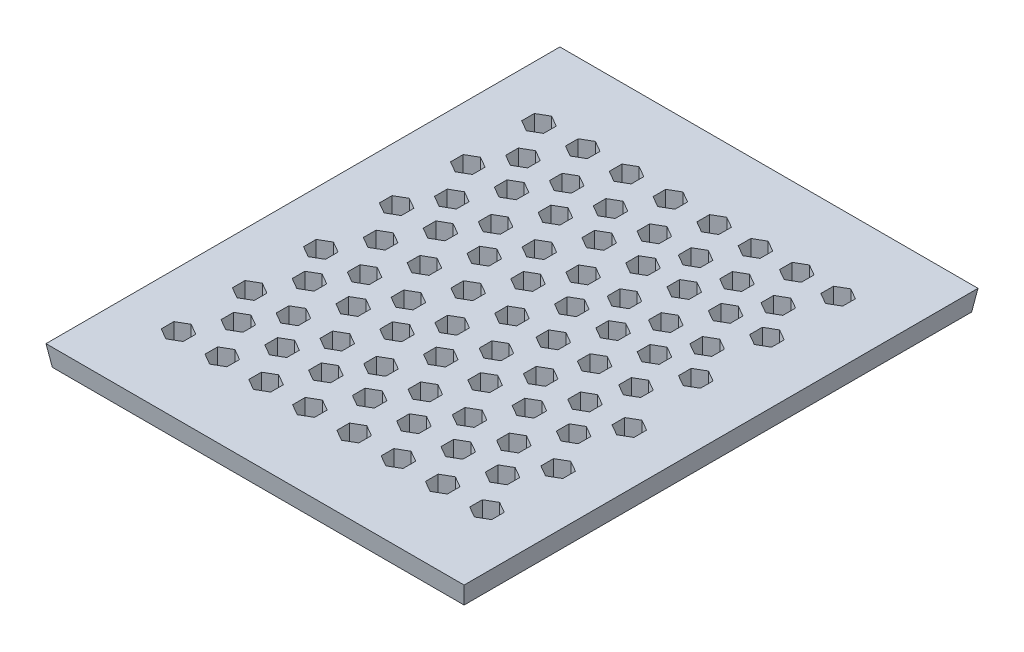
SolidWorks part; units mm, degrees
ref_plane "Front Plane" through (0, 0, 0) normal (0, 0, 1) x (1, 0, 0)
ref_plane "Top Plane" through (0, 0, 0) normal (0, 1, 0) x (1, 0, 0)
ref_plane "Right Plane" through (0, 0, 0) normal (1, 0, 0) x (0, 0, -1)
sketch "Sketch1" plane through (0, 0, 0) normal (0, 1, 0) x (1, 0, 0)
  line L1 (-76.3845, 93.8845) -> (76.3844, 93.8845)
  line L2 (-76.3845, 93.8845) -> (-76.3844, -93.8845)
  line L3 (-76.3844, -93.8845) -> (76.3845, -93.8845)
  line L4 (76.3844, 93.8845) -> (76.3845, -93.8845)
  line L5 (-76.3845, 93.8845) -> (76.3845, -93.8845) construction
  line L6 (-76.3844, -93.8845) -> (76.3844, 93.8845) construction
  point P0 (0, 0)
  dimension "D1" = 187.7689
  dimension "D2" = 152.7689
extrude "Boss-Extrude1" add sketch "Sketch1" against normal blind 7.5 draft 8.77
sketch "Sketch2" plane through (0, 0, 0) normal (0, 1, 0) x (1, 0, 0)
  line L1038 (15.1006, -4.6188) -> (19.1006, -2.3094)
  line L1039 (0, -4.6188) -> (4, -2.3094)
  line L1040 (4, -2.3094) -> (4, 2.3094)
  line L1041 (4, 2.3094) -> (0, 4.6188)
  line L1042 (0, 4.6188) -> (-4, 2.3094)
  line L1043 (-4, 2.3094) -> (-4, -2.3094)
  line L1044 (-4, -2.3094) -> (0, -4.6188)
  line L1045 (11.1006, -2.3094) -> (15.1006, -4.6188)
  line L1046 (8, 18.4752) -> (4, 16.1658)
  line L1047 (4, 16.1658) -> (4, 11.547)
  line L1048 (4, 11.547) -> (8, 9.2376)
  line L1049 (8, 9.2376) -> (12, 11.547)
  line L1050 (12, 11.547) -> (12, 16.1658)
  line L1051 (12, 16.1658) -> (8, 18.4752)
  line L1052 (11.1006, 2.3094) -> (11.1006, -2.3094)
  line L1053 (15.1006, 4.6188) -> (11.1006, 2.3094)
  line L1054 (19.1006, 2.3094) -> (15.1006, 4.6188)
  line L1055 (19.1006, -2.3094) -> (19.1006, 2.3094)
  line L1056 (19.1006, 11.547) -> (23.1006, 9.2376)
  line L1057 (19.1006, 16.1658) -> (19.1006, 11.547)
  line L1058 (23.1006, 18.4752) -> (19.1006, 16.1658)
  line L1059 (27.1006, 16.1658) -> (23.1006, 18.4752)
  line L1060 (27.1006, 11.547) -> (27.1006, 16.1658)
  line L1061 (23.1006, 9.2376) -> (27.1006, 11.547)
  line L1062 (30.2012, -4.6188) -> (34.2012, -2.3094)
  line L1063 (26.2012, -2.3094) -> (30.2012, -4.6188)
  line L1064 (26.2012, 2.3094) -> (26.2012, -2.3094)
  line L1065 (30.2012, 4.6188) -> (26.2012, 2.3094)
  line L1066 (34.2012, 2.3094) -> (30.2012, 4.6188)
  line L1067 (34.2012, -2.3094) -> (34.2012, 2.3094)
  line L1068 (34.2012, 11.547) -> (38.2012, 9.2376)
  line L1069 (34.2012, 16.1658) -> (34.2012, 11.547)
  line L1070 (38.2012, 18.4752) -> (34.2012, 16.1658)
  line L1071 (42.2012, 16.1658) -> (38.2012, 18.4752)
  line L1072 (42.2012, 11.547) -> (42.2012, 16.1658)
  line L1073 (38.2012, 9.2376) -> (42.2012, 11.547)
  line L1074 (45.3017, -4.6188) -> (49.3017, -2.3094)
  line L1075 (41.3017, -2.3094) -> (45.3017, -4.6188)
  line L1076 (41.3017, 2.3094) -> (41.3017, -2.3094)
  line L1077 (45.3017, 4.6188) -> (41.3017, 2.3094)
  line L1078 (49.3017, 2.3094) -> (45.3017, 4.6188)
  line L1079 (49.3017, -2.3094) -> (49.3017, 2.3094)
  line L1080 (49.3017, 11.547) -> (53.3017, 9.2376)
  line L1081 (49.3017, 16.1658) -> (49.3017, 11.547)
  line L1082 (53.3017, 18.4752) -> (49.3017, 16.1658)
  line L1083 (57.3017, 16.1658) -> (53.3017, 18.4752)
  line L1084 (57.3017, 11.547) -> (57.3017, 16.1658)
  line L1085 (53.3017, 9.2376) -> (57.3017, 11.547)
  line L1086 (15.1006, 21.3812) -> (19.1006, 23.6906)
  line L1087 (11.1006, 23.6906) -> (15.1006, 21.3812)
  line L1088 (11.1006, 28.3094) -> (11.1006, 23.6906)
  line L1089 (15.1006, 30.6188) -> (11.1006, 28.3094)
  line L1090 (19.1006, 28.3094) -> (15.1006, 30.6188)
  line L1091 (19.1006, 23.6906) -> (19.1006, 28.3094)
  line L1092 (19.1006, 37.547) -> (23.1006, 35.2376)
  line L1093 (19.1006, 42.1658) -> (19.1006, 37.547)
  line L1094 (23.1006, 44.4752) -> (19.1006, 42.1658)
  line L1095 (27.1006, 42.1658) -> (23.1006, 44.4752)
  line L1096 (27.1006, 37.547) -> (27.1006, 42.1658)
  line L1097 (23.1006, 35.2376) -> (27.1006, 37.547)
  line L1098 (30.2012, 21.3812) -> (34.2012, 23.6906)
  line L1099 (26.2012, 23.6906) -> (30.2012, 21.3812)
  line L1100 (26.2012, 28.3094) -> (26.2012, 23.6906)
  line L1101 (30.2012, 30.6188) -> (26.2012, 28.3094)
  line L1102 (34.2012, 28.3094) -> (30.2012, 30.6188)
  line L1103 (34.2012, 23.6906) -> (34.2012, 28.3094)
  line L1104 (34.2012, 37.547) -> (38.2012, 35.2376)
  line L1105 (34.2012, 42.1658) -> (34.2012, 37.547)
  line L1106 (38.2012, 44.4752) -> (34.2012, 42.1658)
  line L1107 (42.2012, 42.1658) -> (38.2012, 44.4752)
  line L1108 (42.2012, 37.547) -> (42.2012, 42.1658)
  line L1109 (38.2012, 35.2376) -> (42.2012, 37.547)
  line L1110 (45.3017, 21.3812) -> (49.3017, 23.6906)
  line L1111 (41.3017, 23.6906) -> (45.3017, 21.3812)
  line L1112 (41.3017, 28.3094) -> (41.3017, 23.6906)
  line L1113 (45.3017, 30.6188) -> (41.3017, 28.3094)
  line L1114 (49.3017, 28.3094) -> (45.3017, 30.6188)
  line L1115 (49.3017, 23.6906) -> (49.3017, 28.3094)
  line L1116 (49.3017, 37.547) -> (53.3017, 35.2376)
  line L1117 (49.3017, 42.1658) -> (49.3017, 37.547)
  line L1118 (53.3017, 44.4752) -> (49.3017, 42.1658)
  line L1119 (57.3017, 42.1658) -> (53.3017, 44.4752)
  line L1120 (57.3017, 37.547) -> (57.3017, 42.1658)
  line L1121 (53.3017, 35.2376) -> (57.3017, 37.547)
  line L1122 (15.1006, 47.3812) -> (19.1006, 49.6906)
  line L1123 (11.1006, 49.6906) -> (15.1006, 47.3812)
  line L1124 (11.1006, 54.3094) -> (11.1006, 49.6906)
  line L1125 (15.1006, 56.6188) -> (11.1006, 54.3094)
  line L1126 (19.1006, 54.3094) -> (15.1006, 56.6188)
  line L1127 (19.1006, 49.6906) -> (19.1006, 54.3094)
  line L1128 (19.1006, 63.547) -> (23.1006, 61.2376)
  line L1129 (19.1006, 68.1658) -> (19.1006, 63.547)
  line L1130 (23.1006, 70.4752) -> (19.1006, 68.1658)
  line L1131 (27.1006, 68.1658) -> (23.1006, 70.4752)
  line L1132 (27.1006, 63.547) -> (27.1006, 68.1658)
  line L1133 (23.1006, 61.2376) -> (27.1006, 63.547)
  line L1134 (30.2012, 47.3812) -> (34.2012, 49.6906)
  line L1135 (26.2012, 49.6906) -> (30.2012, 47.3812)
  line L1136 (26.2012, 54.3094) -> (26.2012, 49.6906)
  line L1137 (30.2012, 56.6188) -> (26.2012, 54.3094)
  line L1138 (34.2012, 54.3094) -> (30.2012, 56.6188)
  line L1139 (34.2012, 49.6906) -> (34.2012, 54.3094)
  line L1140 (34.2012, 63.547) -> (38.2012, 61.2376)
  line L1141 (34.2012, 68.1658) -> (34.2012, 63.547)
  line L1142 (38.2012, 70.4752) -> (34.2012, 68.1658)
  line L1143 (42.2012, 68.1658) -> (38.2012, 70.4752)
  line L1144 (42.2012, 63.547) -> (42.2012, 68.1658)
  line L1145 (38.2012, 61.2376) -> (42.2012, 63.547)
  line L1146 (45.3017, 47.3812) -> (49.3017, 49.6906)
  line L1147 (41.3017, 49.6906) -> (45.3017, 47.3812)
  line L1148 (41.3017, 54.3094) -> (41.3017, 49.6906)
  line L1149 (45.3017, 56.6188) -> (41.3017, 54.3094)
  line L1150 (49.3017, 54.3094) -> (45.3017, 56.6188)
  line L1151 (49.3017, 49.6906) -> (49.3017, 54.3094)
  line L1152 (49.3017, 63.547) -> (53.3017, 61.2376)
  line L1153 (49.3017, 68.1658) -> (49.3017, 63.547)
  line L1154 (53.3017, 70.4752) -> (49.3017, 68.1658)
  line L1155 (57.3017, 68.1658) -> (53.3017, 70.4752)
  line L1156 (57.3017, 63.547) -> (57.3017, 68.1658)
  line L1157 (53.3017, 61.2376) -> (57.3017, 63.547)
  line L1159 (-4, 23.6906) -> (0, 21.3812)
  line L1160 (-4, 28.3094) -> (-4, 23.6906)
  line L1161 (0, 30.6188) -> (-4, 28.3094)
  line L1162 (4, 28.3094) -> (0, 30.6188)
  line L1163 (4, 23.6906) -> (4, 28.3094)
  line L1164 (4, 37.547) -> (8, 35.2376)
  line L1165 (4, 42.1658) -> (4, 37.547)
  line L1166 (8, 44.4752) -> (4, 42.1658)
  line L1167 (12, 42.1658) -> (8, 44.4752)
  line L1168 (12, 37.547) -> (12, 42.1658)
  line L1170 (0, 47.3812) -> (4, 49.6906)
  line L1171 (-4, 49.6906) -> (0, 47.3812)
  line L1172 (-4, 54.3094) -> (-4, 49.6906)
  line L1174 (4, 54.3094) -> (0, 56.6188)
  line L1175 (4, 49.6906) -> (4, 54.3094)
  line L1176 (4, 63.547) -> (8, 61.2376)
  line L1178 (8, 70.4752) -> (4, 68.1658)
  line L1179 (12, 68.1658) -> (8, 70.4752)
  line L1180 (12, 63.547) -> (12, 68.1658)
  line L1181 (8, 61.2376) -> (12, 63.547)
  line L1182 (-20, -2.3094) -> (-16, -4.6188)
  line L1183 (-20, 2.3094) -> (-20, -2.3094)
  line L1184 (-16, 4.6188) -> (-20, 2.3094)
  line L1185 (-12, 2.3094) -> (-16, 4.6188)
  line L1186 (-16, -4.6188) -> (-12, -2.3094)
  line L1187 (-12, -2.3094) -> (-12, 2.3094)
  line L1188 (-12, 11.547) -> (-8, 9.2376)
  line L1189 (-12, 16.1658) -> (-12, 11.547)
  line L1190 (-8, 18.4752) -> (-12, 16.1658)
  line L1191 (-4, 16.1658) -> (-8, 18.4752)
  line L1192 (-4, 11.547) -> (-4, 16.1658)
  line L1193 (-8, 9.2376) -> (-4, 11.547)
  line L1194 (-36, -2.3094) -> (-32, -4.6188)
  line L1195 (-36, 2.3094) -> (-36, -2.3094)
  line L1196 (-32, 4.6188) -> (-36, 2.3094)
  line L1197 (-28, 2.3094) -> (-32, 4.6188)
  line L1198 (-32, -4.6188) -> (-28, -2.3094)
  line L1199 (-28, -2.3094) -> (-28, 2.3094)
  line L1200 (-28, 11.547) -> (-24, 9.2376)
  line L1201 (-28, 16.1658) -> (-28, 11.547)
  line L1202 (-24, 18.4752) -> (-28, 16.1658)
  line L1203 (-20, 16.1658) -> (-24, 18.4752)
  line L1204 (-20, 11.547) -> (-20, 16.1658)
  line L1205 (-24, 9.2376) -> (-20, 11.547)
  line L1206 (-52, -2.3094) -> (-48, -4.6188)
  line L1207 (-52, 2.3094) -> (-52, -2.3094)
  line L1208 (-48, 4.6188) -> (-52, 2.3094)
  line L1209 (-44, 2.3094) -> (-48, 4.6188)
  line L1210 (-48, -4.6188) -> (-44, -2.3094)
  line L1211 (-44, -2.3094) -> (-44, 2.3094)
  line L1212 (-44, 11.547) -> (-40, 9.2376)
  line L1213 (-44, 16.1658) -> (-44, 11.547)
  line L1214 (-40, 18.4752) -> (-44, 16.1658)
  line L1215 (-36, 16.1658) -> (-40, 18.4752)
  line L1216 (-36, 11.547) -> (-36, 16.1658)
  line L1217 (-40, 9.2376) -> (-36, 11.547)
  line L1224 (-60, 11.547) -> (-56, 9.2376)
  line L1225 (-60, 16.1658) -> (-60, 11.547)
  line L1226 (-56, 18.4752) -> (-60, 16.1658)
  line L1227 (-52, 16.1658) -> (-56, 18.4752)
  line L1228 (-52, 11.547) -> (-52, 16.1658)
  line L1229 (-56, 9.2376) -> (-52, 11.547)
  line L1230 (-20, 23.6906) -> (-16, 21.3812)
  line L1231 (-20, 28.3094) -> (-20, 23.6906)
  line L1232 (-16, 30.6188) -> (-20, 28.3094)
  line L1233 (-12, 28.3094) -> (-16, 30.6188)
  line L1234 (-16, 21.3812) -> (-12, 23.6906)
  line L1235 (-12, 23.6906) -> (-12, 28.3094)
  line L1236 (-12, 37.547) -> (-8, 35.2376)
  line L1237 (-12, 42.1658) -> (-12, 37.547)
  line L1238 (-8, 44.4752) -> (-12, 42.1658)
  line L1239 (-4, 42.1658) -> (-8, 44.4752)
  line L1240 (-4, 37.547) -> (-4, 42.1658)
  line L1241 (-8, 35.2376) -> (-4, 37.547)
  line L1242 (-36, 23.6906) -> (-32, 21.3812)
  line L1243 (-36, 28.3094) -> (-36, 23.6906)
  line L1244 (-32, 30.6188) -> (-36, 28.3094)
  line L1245 (-28, 28.3094) -> (-32, 30.6188)
  line L1246 (-32, 21.3812) -> (-28, 23.6906)
  line L1247 (-28, 23.6906) -> (-28, 28.3094)
  line L1248 (-28, 37.547) -> (-24, 35.2376)
  line L1249 (-28, 42.1658) -> (-28, 37.547)
  line L1250 (-24, 44.4752) -> (-28, 42.1658)
  line L1251 (-20, 42.1658) -> (-24, 44.4752)
  line L1252 (-20, 37.547) -> (-20, 42.1658)
  line L1253 (-24, 35.2376) -> (-20, 37.547)
  line L1254 (-52, 23.6906) -> (-48, 21.3812)
  line L1255 (-52, 28.3094) -> (-52, 23.6906)
  line L1256 (-48, 30.6188) -> (-52, 28.3094)
  line L1257 (-44, 28.3094) -> (-48, 30.6188)
  line L1258 (-48, 21.3812) -> (-44, 23.6906)
  line L1259 (-44, 23.6906) -> (-44, 28.3094)
  line L1260 (-44, 37.547) -> (-40, 35.2376)
  line L1261 (-44, 42.1658) -> (-44, 37.547)
  line L1262 (-40, 44.4752) -> (-44, 42.1658)
  line L1263 (-36, 42.1658) -> (-40, 44.4752)
  line L1264 (-36, 37.547) -> (-36, 42.1658)
  line L1265 (-40, 35.2376) -> (-36, 37.547)
  line L1272 (-60, 37.547) -> (-56, 35.2376)
  line L1273 (-60, 42.1658) -> (-60, 37.547)
  line L1274 (-56, 44.4752) -> (-60, 42.1658)
  line L1275 (-52, 42.1658) -> (-56, 44.4752)
  line L1276 (-52, 37.547) -> (-52, 42.1658)
  line L1277 (-56, 35.2376) -> (-52, 37.547)
  line L1278 (-20, 49.6906) -> (-16, 47.3812)
  line L1279 (-20, 54.3094) -> (-20, 49.6906)
  line L1280 (-16, 56.6188) -> (-20, 54.3094)
  line L1281 (-12, 54.3094) -> (-16, 56.6188)
  line L1282 (-16, 47.3812) -> (-12, 49.6906)
  line L1283 (-12, 49.6906) -> (-12, 54.3094)
  line L1284 (-12, 63.547) -> (-8, 61.2376)
  line L1285 (-12, 68.1658) -> (-12, 63.547)
  line L1286 (-8, 70.4752) -> (-12, 68.1658)
  line L1287 (-4, 68.1658) -> (-8, 70.4752)
  line L1288 (-4, 63.547) -> (-4, 68.1658)
  line L1289 (-8, 61.2376) -> (-4, 63.547)
  line L1290 (-36, 49.6906) -> (-32, 47.3812)
  line L1291 (-36, 54.3094) -> (-36, 49.6906)
  line L1292 (-32, 56.6188) -> (-36, 54.3094)
  line L1293 (-28, 54.3094) -> (-32, 56.6188)
  line L1294 (-32, 47.3812) -> (-28, 49.6906)
  line L1295 (-28, 49.6906) -> (-28, 54.3094)
  line L1296 (-28, 63.547) -> (-24, 61.2376)
  line L1297 (-28, 68.1658) -> (-28, 63.547)
  line L1298 (-24, 70.4752) -> (-28, 68.1658)
  line L1299 (-20, 68.1658) -> (-24, 70.4752)
  line L1300 (-20, 63.547) -> (-20, 68.1658)
  line L1301 (-24, 61.2376) -> (-20, 63.547)
  line L1302 (-52, 49.6906) -> (-48, 47.3812)
  line L1303 (-52, 54.3094) -> (-52, 49.6906)
  line L1304 (-48, 56.6188) -> (-52, 54.3094)
  line L1305 (-44, 54.3094) -> (-48, 56.6188)
  line L1306 (-48, 47.3812) -> (-44, 49.6906)
  line L1307 (-44, 49.6906) -> (-44, 54.3094)
  line L1308 (-44, 63.547) -> (-40, 61.2376)
  line L1309 (-44, 68.1658) -> (-44, 63.547)
  line L1310 (-40, 70.4752) -> (-44, 68.1658)
  line L1311 (-36, 68.1658) -> (-40, 70.4752)
  line L1312 (-36, 63.547) -> (-36, 68.1658)
  line L1313 (-40, 61.2376) -> (-36, 63.547)
  line L1320 (-60, 63.547) -> (-56, 61.2376)
  line L1321 (-60, 68.1658) -> (-60, 63.547)
  line L1322 (-56, 70.4752) -> (-60, 68.1658)
  line L1323 (-52, 68.1658) -> (-56, 70.4752)
  line L1324 (-52, 63.547) -> (-52, 68.1658)
  line L1325 (-56, 61.2376) -> (-52, 63.547)
  line L1330 (0, 21.3812) -> (4, 23.6906)
  line L1337 (8, 35.2376) -> (12, 37.547)
  line L1340 (0, 56.6188) -> (-4, 54.3094)
  line L1345 (4, 68.1658) -> (4, 63.547)
  line L1352 (-68, 49.6906) -> (-64, 47.3812) [skipped]
  line L1353 (-68, 54.3094) -> (-68, 49.6906) [skipped]
  line L1354 (-64, 56.6188) -> (-68, 54.3094) [skipped]
  line L1355 (-60, 54.3094) -> (-64, 56.6188) [skipped]
  line L1356 (-64, 47.3812) -> (-60, 49.6906) [skipped]
  line L1357 (-60, 49.6906) -> (-60, 54.3094) [skipped]
  line L1358 (-68, 23.6906) -> (-64, 21.3812) [skipped]
  line L1359 (-68, 28.3094) -> (-68, 23.6906) [skipped]
  line L1360 (-64, 30.6188) -> (-68, 28.3094) [skipped]
  line L1361 (-60, 28.3094) -> (-64, 30.6188) [skipped]
  line L1362 (-64, 21.3812) -> (-60, 23.6906) [skipped]
  line L1363 (-60, 23.6906) -> (-60, 28.3094) [skipped]
  line L1364 (-68, -2.3094) -> (-64, -4.6188) [skipped]
  line L1365 (-68, 2.3094) -> (-68, -2.3094) [skipped]
  line L1366 (-64, 4.6188) -> (-68, 2.3094) [skipped]
  line L1367 (-60, 2.3094) -> (-64, 4.6188) [skipped]
  line L1368 (-64, -4.6188) -> (-60, -2.3094) [skipped]
  line L1369 (-60, -2.3094) -> (-60, 2.3094) [skipped]
  line L1370 (-8, -9.2376) -> (-12, -11.547)
  line L1371 (-12, -11.547) -> (-12, -16.1658)
  line L1372 (-12, -16.1658) -> (-8, -18.4752)
  line L1373 (-8, -18.4752) -> (-4, -16.1658)
  line L1374 (-4, -16.1658) -> (-4, -11.547)
  line L1375 (-4, -11.547) -> (-8, -9.2376)
  line L1380 (12.1801, -11.547) -> (8.1801, -9.2376)
  line L1381 (8.1801, -9.2376) -> (4.1801, -11.547)
  line L1382 (4.1801, -11.547) -> (4.1801, -16.1658)
  line L1383 (4.1801, -16.1658) -> (8.1801, -18.4752)
  line L1384 (8.1801, -18.4752) -> (12.1801, -16.1658)
  line L1385 (12.1801, -16.1658) -> (12.1801, -11.547)
  line L1392 (28.3602, -11.547) -> (24.3602, -9.2376)
  line L1393 (24.3602, -9.2376) -> (20.3602, -11.547)
  line L1394 (20.3602, -11.547) -> (20.3602, -16.1658)
  line L1395 (20.3602, -16.1658) -> (24.3602, -18.4752)
  line L1396 (24.3602, -18.4752) -> (28.3602, -16.1658)
  line L1397 (28.3602, -16.1658) -> (28.3602, -11.547)
  line L1404 (44.5404, -11.547) -> (40.5404, -9.2376)
  line L1405 (40.5404, -9.2376) -> (36.5404, -11.547)
  line L1406 (36.5404, -11.547) -> (36.5404, -16.1658)
  line L1407 (36.5404, -16.1658) -> (40.5404, -18.4752)
  line L1408 (40.5404, -18.4752) -> (44.5404, -16.1658)
  line L1409 (44.5404, -16.1658) -> (44.5404, -11.547)
  line L1416 (60.7205, -11.547) -> (56.7205, -9.2376)
  line L1417 (56.7205, -9.2376) -> (52.7205, -11.547)
  line L1418 (52.7205, -11.547) -> (52.7205, -16.1658)
  line L1419 (52.7205, -16.1658) -> (56.7205, -18.4752)
  line L1420 (56.7205, -18.4752) -> (60.7205, -16.1658)
  line L1421 (60.7205, -16.1658) -> (60.7205, -11.547)
  line L1422 (12.1801, -28.3094) -> (16.1801, -30.6188)
  line L1423 (12.1801, -23.6906) -> (12.1801, -28.3094)
  line L1424 (16.1801, -21.3812) -> (12.1801, -23.6906)
  line L1425 (20.1801, -23.6906) -> (16.1801, -21.3812)
  line L1426 (20.1801, -28.3094) -> (20.1801, -23.6906)
  line L1427 (16.1801, -30.6188) -> (20.1801, -28.3094)
  line L1428 (12.1801, -37.547) -> (8.1801, -35.2376)
  line L1429 (8.1801, -35.2376) -> (4.1801, -37.547)
  line L1430 (4.1801, -37.547) -> (4.1801, -42.1658)
  line L1431 (4.1801, -42.1658) -> (8.1801, -44.4752)
  line L1432 (8.1801, -44.4752) -> (12.1801, -42.1658)
  line L1433 (12.1801, -42.1658) -> (12.1801, -37.547)
  line L1434 (28.3602, -28.3094) -> (32.3602, -30.6188)
  line L1435 (28.3602, -23.6906) -> (28.3602, -28.3094)
  line L1436 (32.3602, -21.3812) -> (28.3602, -23.6906)
  line L1437 (36.3602, -23.6906) -> (32.3602, -21.3812)
  line L1438 (36.3602, -28.3094) -> (36.3602, -23.6906)
  line L1439 (32.3602, -30.6188) -> (36.3602, -28.3094)
  line L1440 (28.3602, -37.547) -> (24.3602, -35.2376)
  line L1441 (24.3602, -35.2376) -> (20.3602, -37.547)
  line L1442 (20.3602, -37.547) -> (20.3602, -42.1658)
  line L1443 (20.3602, -42.1658) -> (24.3602, -44.4752)
  line L1444 (24.3602, -44.4752) -> (28.3602, -42.1658)
  line L1445 (28.3602, -42.1658) -> (28.3602, -37.547)
  line L1446 (44.5404, -28.3094) -> (48.5404, -30.6188)
  line L1447 (44.5404, -23.6906) -> (44.5404, -28.3094)
  line L1448 (48.5404, -21.3812) -> (44.5404, -23.6906)
  line L1449 (52.5404, -23.6906) -> (48.5404, -21.3812)
  line L1450 (52.5404, -28.3094) -> (52.5404, -23.6906)
  line L1451 (48.5404, -30.6188) -> (52.5404, -28.3094)
  line L1452 (44.5404, -37.547) -> (40.5404, -35.2376)
  line L1453 (40.5404, -35.2376) -> (36.5404, -37.547)
  line L1454 (36.5404, -37.547) -> (36.5404, -42.1658)
  line L1455 (36.5404, -42.1658) -> (40.5404, -44.4752)
  line L1456 (40.5404, -44.4752) -> (44.5404, -42.1658)
  line L1457 (44.5404, -42.1658) -> (44.5404, -37.547)
  line L1464 (60.7205, -37.547) -> (56.7205, -35.2376)
  line L1465 (56.7205, -35.2376) -> (52.7205, -37.547)
  line L1466 (52.7205, -37.547) -> (52.7205, -42.1658)
  line L1467 (52.7205, -42.1658) -> (56.7205, -44.4752)
  line L1468 (56.7205, -44.4752) -> (60.7205, -42.1658)
  line L1469 (60.7205, -42.1658) -> (60.7205, -37.547)
  line L1470 (12.1801, -54.3094) -> (16.1801, -56.6188)
  line L1471 (12.1801, -49.6906) -> (12.1801, -54.3094)
  line L1472 (16.1801, -47.3812) -> (12.1801, -49.6906)
  line L1473 (20.1801, -49.6906) -> (16.1801, -47.3812)
  line L1474 (20.1801, -54.3094) -> (20.1801, -49.6906)
  line L1475 (16.1801, -56.6188) -> (20.1801, -54.3094)
  line L1476 (12.1801, -63.547) -> (8.1801, -61.2376)
  line L1477 (8.1801, -61.2376) -> (4.1801, -63.547)
  line L1478 (4.1801, -63.547) -> (4.1801, -68.1658)
  line L1479 (4.1801, -68.1658) -> (8.1801, -70.4752)
  line L1480 (8.1801, -70.4752) -> (12.1801, -68.1658)
  line L1481 (12.1801, -68.1658) -> (12.1801, -63.547)
  line L1482 (28.3602, -54.3094) -> (32.3602, -56.6188)
  line L1483 (28.3602, -49.6906) -> (28.3602, -54.3094)
  line L1484 (32.3602, -47.3812) -> (28.3602, -49.6906)
  line L1485 (36.3602, -49.6906) -> (32.3602, -47.3812)
  line L1486 (36.3602, -54.3094) -> (36.3602, -49.6906)
  line L1487 (32.3602, -56.6188) -> (36.3602, -54.3094)
  line L1488 (28.3602, -63.547) -> (24.3602, -61.2376)
  line L1489 (24.3602, -61.2376) -> (20.3602, -63.547)
  line L1490 (20.3602, -63.547) -> (20.3602, -68.1658)
  line L1491 (20.3602, -68.1658) -> (24.3602, -70.4752)
  line L1492 (24.3602, -70.4752) -> (28.3602, -68.1658)
  line L1493 (28.3602, -68.1658) -> (28.3602, -63.547)
  line L1494 (44.5404, -54.3094) -> (48.5404, -56.6188)
  line L1495 (44.5404, -49.6906) -> (44.5404, -54.3094)
  line L1496 (48.5404, -47.3812) -> (44.5404, -49.6906)
  line L1497 (52.5404, -49.6906) -> (48.5404, -47.3812)
  line L1498 (52.5404, -54.3094) -> (52.5404, -49.6906)
  line L1499 (48.5404, -56.6188) -> (52.5404, -54.3094)
  line L1500 (44.5404, -63.547) -> (40.5404, -61.2376)
  line L1501 (40.5404, -61.2376) -> (36.5404, -63.547)
  line L1502 (36.5404, -63.547) -> (36.5404, -68.1658)
  line L1503 (36.5404, -68.1658) -> (40.5404, -70.4752)
  line L1504 (40.5404, -70.4752) -> (44.5404, -68.1658)
  line L1505 (44.5404, -68.1658) -> (44.5404, -63.547)
  line L1512 (60.7205, -63.547) -> (56.7205, -61.2376)
  line L1513 (56.7205, -61.2376) -> (52.7205, -63.547)
  line L1514 (52.7205, -63.547) -> (52.7205, -68.1658)
  line L1515 (52.7205, -68.1658) -> (56.7205, -70.4752)
  line L1516 (56.7205, -70.4752) -> (60.7205, -68.1658)
  line L1517 (60.7205, -68.1658) -> (60.7205, -63.547)
  line L1518 (-4, -28.3094) -> (0, -30.6188)
  line L1519 (-4, -23.6906) -> (-4, -28.3094)
  line L1520 (0, -21.3812) -> (-4, -23.6906)
  line L1521 (4, -23.6906) -> (0, -21.3812)
  line L1522 (4, -28.3094) -> (4, -23.6906)
  line L1523 (0, -30.6188) -> (4, -28.3094)
  line L1524 (-4, -37.547) -> (-8, -35.2376)
  line L1525 (-8, -35.2376) -> (-12, -37.547)
  line L1526 (-12, -37.547) -> (-12, -42.1658)
  line L1527 (-12, -42.1658) -> (-8, -44.4752)
  line L1529 (-4, -42.1658) -> (-4, -37.547)
  line L1530 (-4, -54.3094) -> (0, -56.6188)
  line L1531 (-4, -49.6906) -> (-4, -54.3094)
  line L1532 (0, -47.3812) -> (-4, -49.6906)
  line L1533 (4, -49.6906) -> (0, -47.3812)
  line L1534 (4, -54.3094) -> (4, -49.6906)
  line L1536 (-4, -63.547) -> (-8, -61.2376)
  line L1537 (-8, -61.2376) -> (-12, -63.547)
  line L1538 (-12, -63.547) -> (-12, -68.1658)
  line L1539 (-12, -68.1658) -> (-8, -70.4752)
  line L1541 (-4, -68.1658) -> (-4, -63.547)
  line L1542 (-20, -11.547) -> (-24, -9.2376)
  line L1543 (-24, -9.2376) -> (-28, -11.547)
  line L1544 (-28, -11.547) -> (-28, -16.1658)
  line L1545 (-28, -16.1658) -> (-24, -18.4752)
  line L1546 (-24, -18.4752) -> (-20, -16.1658)
  line L1547 (-20, -16.1658) -> (-20, -11.547)
  line L1548 (-20, -23.6906) -> (-20, -28.3094)
  line L1549 (-16, -21.3812) -> (-20, -23.6906)
  line L1550 (-12, -23.6906) -> (-16, -21.3812)
  line L1551 (-12, -28.3094) -> (-12, -23.6906)
  line L1552 (-16, -30.6188) -> (-12, -28.3094)
  line L1553 (-20, -28.3094) -> (-16, -30.6188)
  line L1554 (-36, -11.547) -> (-40, -9.2376)
  line L1555 (-40, -9.2376) -> (-44, -11.547)
  line L1556 (-44, -11.547) -> (-44, -16.1658)
  line L1557 (-44, -16.1658) -> (-40, -18.4752)
  line L1558 (-40, -18.4752) -> (-36, -16.1658)
  line L1559 (-36, -16.1658) -> (-36, -11.547)
  line L1560 (-36, -23.6906) -> (-36, -28.3094)
  line L1561 (-32, -21.3812) -> (-36, -23.6906)
  line L1562 (-28, -23.6906) -> (-32, -21.3812)
  line L1563 (-28, -28.3094) -> (-28, -23.6906)
  line L1564 (-32, -30.6188) -> (-28, -28.3094)
  line L1565 (-36, -28.3094) -> (-32, -30.6188)
  line L1566 (-52, -11.547) -> (-56, -9.2376)
  line L1567 (-56, -9.2376) -> (-60, -11.547)
  line L1568 (-60, -11.547) -> (-60, -16.1658)
  line L1569 (-60, -16.1658) -> (-56, -18.4752)
  line L1570 (-56, -18.4752) -> (-52, -16.1658)
  line L1571 (-52, -16.1658) -> (-52, -11.547)
  line L1572 (-52, -23.6906) -> (-52, -28.3094)
  line L1573 (-48, -21.3812) -> (-52, -23.6906)
  line L1574 (-44, -23.6906) -> (-48, -21.3812)
  line L1575 (-44, -28.3094) -> (-44, -23.6906)
  line L1576 (-48, -30.6188) -> (-44, -28.3094)
  line L1577 (-52, -28.3094) -> (-48, -30.6188)
  line L1578 (-20, -37.547) -> (-24, -35.2376)
  line L1579 (-24, -35.2376) -> (-28, -37.547)
  line L1580 (-28, -37.547) -> (-28, -42.1658)
  line L1581 (-28, -42.1658) -> (-24, -44.4752)
  line L1582 (-24, -44.4752) -> (-20, -42.1658)
  line L1583 (-20, -42.1658) -> (-20, -37.547)
  line L1584 (-20, -49.6906) -> (-20, -54.3094)
  line L1585 (-16, -47.3812) -> (-20, -49.6906)
  line L1586 (-12, -49.6906) -> (-16, -47.3812)
  line L1587 (-12, -54.3094) -> (-12, -49.6906)
  line L1588 (-16, -56.6188) -> (-12, -54.3094)
  line L1589 (-20, -54.3094) -> (-16, -56.6188)
  line L1590 (-36, -37.547) -> (-40, -35.2376)
  line L1591 (-40, -35.2376) -> (-44, -37.547)
  line L1592 (-44, -37.547) -> (-44, -42.1658)
  line L1593 (-44, -42.1658) -> (-40, -44.4752)
  line L1594 (-40, -44.4752) -> (-36, -42.1658)
  line L1595 (-36, -42.1658) -> (-36, -37.547)
  line L1596 (-36, -49.6906) -> (-36, -54.3094)
  line L1597 (-32, -47.3812) -> (-36, -49.6906)
  line L1598 (-28, -49.6906) -> (-32, -47.3812)
  line L1599 (-28, -54.3094) -> (-28, -49.6906)
  line L1600 (-32, -56.6188) -> (-28, -54.3094)
  line L1601 (-36, -54.3094) -> (-32, -56.6188)
  line L1602 (-52, -37.547) -> (-56, -35.2376)
  line L1603 (-56, -35.2376) -> (-60, -37.547)
  line L1604 (-60, -37.547) -> (-60, -42.1658)
  line L1605 (-60, -42.1658) -> (-56, -44.4752)
  line L1606 (-56, -44.4752) -> (-52, -42.1658)
  line L1607 (-52, -42.1658) -> (-52, -37.547)
  line L1608 (-52, -49.6906) -> (-52, -54.3094)
  line L1609 (-48, -47.3812) -> (-52, -49.6906)
  line L1610 (-44, -49.6906) -> (-48, -47.3812)
  line L1611 (-44, -54.3094) -> (-44, -49.6906)
  line L1612 (-48, -56.6188) -> (-44, -54.3094)
  line L1613 (-52, -54.3094) -> (-48, -56.6188)
  line L1614 (-20, -63.547) -> (-24, -61.2376)
  line L1615 (-24, -61.2376) -> (-28, -63.547)
  line L1616 (-28, -63.547) -> (-28, -68.1658)
  line L1617 (-28, -68.1658) -> (-24, -70.4752)
  line L1618 (-24, -70.4752) -> (-20, -68.1658)
  line L1619 (-20, -68.1658) -> (-20, -63.547)
  line L1626 (-36, -63.547) -> (-40, -61.2376)
  line L1627 (-40, -61.2376) -> (-44, -63.547)
  line L1628 (-44, -63.547) -> (-44, -68.1658)
  line L1629 (-44, -68.1658) -> (-40, -70.4752)
  line L1630 (-40, -70.4752) -> (-36, -68.1658)
  line L1631 (-36, -68.1658) -> (-36, -63.547)
  line L1638 (-52, -63.547) -> (-56, -61.2376)
  line L1639 (-56, -61.2376) -> (-60, -63.547)
  line L1640 (-60, -63.547) -> (-60, -68.1658)
  line L1641 (-60, -68.1658) -> (-56, -70.4752)
  line L1642 (-56, -70.4752) -> (-52, -68.1658)
  line L1643 (-52, -68.1658) -> (-52, -63.547)
  line L1654 (-8, -44.4752) -> (-4, -42.1658)
  line L1660 (0, -56.6188) -> (4, -54.3094)
  line L1666 (-8, -70.4752) -> (-4, -68.1658)
  line L1674 (-20, -75.6906) -> (-20, -80.3094) [skipped]
  line L1675 (-16, -73.3812) -> (-20, -75.6906) [skipped]
  line L1676 (-12, -75.6906) -> (-16, -73.3812) [skipped]
  line L1677 (-12, -80.3094) -> (-12, -75.6906) [skipped]
  line L1678 (-16, -82.6188) -> (-12, -80.3094) [skipped]
  line L1679 (-20, -80.3094) -> (-16, -82.6188) [skipped]
  line L1680 (-36, -75.6906) -> (-36, -80.3094) [skipped]
  line L1681 (-32, -73.3812) -> (-36, -75.6906) [skipped]
  line L1682 (-28, -75.6906) -> (-32, -73.3812) [skipped]
  line L1683 (-28, -80.3094) -> (-28, -75.6906) [skipped]
  line L1684 (-32, -82.6188) -> (-28, -80.3094) [skipped]
  line L1685 (-36, -80.3094) -> (-32, -82.6188) [skipped]
  line L1686 (-52, -75.6906) -> (-52, -80.3094) [skipped]
  line L1687 (-48, -73.3812) -> (-52, -75.6906) [skipped]
  line L1688 (-44, -75.6906) -> (-48, -73.3812) [skipped]
  line L1689 (-44, -80.3094) -> (-44, -75.6906) [skipped]
  line L1690 (-48, -82.6188) -> (-44, -80.3094) [skipped]
  line L1691 (-52, -80.3094) -> (-48, -82.6188) [skipped]
  line L1692 (-4, -75.6906) -> (-4, -80.3094) [skipped]
  line L1693 (0, -73.3812) -> (-4, -75.6906) [skipped]
  line L1694 (4, -75.6906) -> (0, -73.3812) [skipped]
  line L1695 (4, -80.3094) -> (4, -75.6906) [skipped]
  line L1696 (0, -82.6188) -> (4, -80.3094) [skipped]
  line L1697 (-4, -80.3094) -> (0, -82.6188) [skipped]
  line L1698 (60.7205, -2.3094) -> (64.7205, -4.6188) [skipped]
  line L1699 (60.7205, 2.3094) -> (60.7205, -2.3094) [skipped]
  line L1700 (64.7205, 4.6188) -> (60.7205, 2.3094) [skipped]
  line L1701 (68.7205, 2.3094) -> (64.7205, 4.6188) [skipped]
  line L1702 (68.7205, -2.3094) -> (68.7205, 2.3094) [skipped]
  line L1703 (64.7205, -4.6188) -> (68.7205, -2.3094) [skipped]
  line L1704 (60.7205, -28.3094) -> (64.7205, -30.6188) [skipped]
  line L1705 (60.7205, -23.6906) -> (60.7205, -28.3094) [skipped]
  line L1706 (64.7205, -21.3812) -> (60.7205, -23.6906) [skipped]
  line L1707 (68.7205, -23.6906) -> (64.7205, -21.3812) [skipped]
  line L1708 (68.7205, -28.3094) -> (68.7205, -23.6906) [skipped]
  line L1709 (64.7205, -30.6188) -> (68.7205, -28.3094) [skipped]
  line L1710 (60.7205, -54.3094) -> (64.7205, -56.6188) [skipped]
  line L1711 (60.7205, -49.6906) -> (60.7205, -54.3094) [skipped]
  line L1712 (64.7205, -47.3812) -> (60.7205, -49.6906) [skipped]
  line L1713 (68.7205, -49.6906) -> (64.7205, -47.3812) [skipped]
  line L1714 (68.7205, -54.3094) -> (68.7205, -49.6906) [skipped]
  line L1715 (64.7205, -56.6188) -> (68.7205, -54.3094) [skipped]
  line L1716 (16.1801, -4.6188) -> (20.1801, -2.3094) [skipped]
  line L1717 (12.1801, -2.3094) -> (16.1801, -4.6188) [skipped]
  line L1718 (12.1801, 2.3094) -> (12.1801, -2.3094) [skipped]
  line L1719 (16.1801, 4.6188) -> (12.1801, 2.3094) [skipped]
  line L1720 (20.1801, 2.3094) -> (16.1801, 4.6188) [skipped]
  line L1721 (20.1801, -2.3094) -> (20.1801, 2.3094) [skipped]
  line L1722 (32.3602, -4.6188) -> (36.3602, -2.3094) [skipped]
  line L1723 (28.3602, -2.3094) -> (32.3602, -4.6188) [skipped]
  line L1724 (28.3602, 2.3094) -> (28.3602, -2.3094) [skipped]
  line L1725 (32.3602, 4.6188) -> (28.3602, 2.3094) [skipped]
  line L1726 (36.3602, 2.3094) -> (32.3602, 4.6188) [skipped]
  line L1727 (36.3602, -2.3094) -> (36.3602, 2.3094) [skipped]
  line L1728 (44.5404, -2.3094) -> (48.5404, -4.6188) [skipped]
  line L1729 (44.5404, 2.3094) -> (44.5404, -2.3094) [skipped]
  line L1730 (48.5404, 4.6188) -> (44.5404, 2.3094) [skipped]
  line L1731 (52.5404, 2.3094) -> (48.5404, 4.6188) [skipped]
  line L1732 (52.5404, -2.3094) -> (52.5404, 2.3094) [skipped]
  line L1733 (48.5404, -4.6188) -> (52.5404, -2.3094) [skipped]
  line L1734 (-8, -70.4752) -> (-4, -68.1658) [skipped]
  line L1735 (0, -56.6188) -> (4, -54.3094) [skipped]
  line L1736 (-8, -44.4752) -> (-4, -42.1658) [skipped]
  line L1737 (0, 21.3812) -> (4, 23.6906) [skipped]
  line L1738 (8, 35.2376) -> (12, 37.547) [skipped]
  line L1739 (0, 56.6188) -> (-4, 54.3094) [skipped]
  line L1740 (4, 68.1658) -> (4, 63.547) [skipped]
  line L1741 (4, -54.3094) -> (4, -49.6906) [skipped]
  line L1742 (4, 23.6906) -> (4, 28.3094) [skipped]
  line L1743 (4, 42.1658) -> (4, 37.547) [skipped]
  line L1744 (4, 49.6906) -> (4, 54.3094) [skipped]
  line L1745 (-4, 54.3094) -> (-4, 49.6906) [skipped]
  line L1746 (-4, 28.3094) -> (-4, 23.6906) [skipped]
  line L1747 (-4, -42.1658) -> (-4, -37.547) [skipped]
  line L1748 (-4, -49.6906) -> (-4, -54.3094) [skipped]
  line L1749 (-4, -68.1658) -> (-4, -63.547) [skipped]
  line L1750 (12, 37.547) -> (12, 42.1658) [skipped]
  line L1751 (12, 63.547) -> (12, 68.1658) [skipped]
  line L1752 (-4, 23.6906) -> (0, 21.3812) [skipped]
  line L1753 (0, 30.6188) -> (-4, 28.3094) [skipped]
  line L1754 (4, 28.3094) -> (0, 30.6188) [skipped]
  line L1755 (4, 37.547) -> (8, 35.2376) [skipped]
  line L1756 (8, 44.4752) -> (4, 42.1658) [skipped]
  line L1757 (12, 42.1658) -> (8, 44.4752) [skipped]
  line L1758 (0, 47.3812) -> (4, 49.6906) [skipped]
  line L1759 (-4, 49.6906) -> (0, 47.3812) [skipped]
  line L1760 (4, 54.3094) -> (0, 56.6188) [skipped]
  line L1761 (4, 63.547) -> (8, 61.2376) [skipped]
  line L1762 (8, 70.4752) -> (4, 68.1658) [skipped]
  line L1763 (12, 68.1658) -> (8, 70.4752) [skipped]
  line L1764 (8, 61.2376) -> (12, 63.547) [skipped]
  line L1765 (-12, -63.547) -> (-12, -68.1658) [skipped]
  line L1766 (-12, -37.547) -> (-12, -42.1658) [skipped]
  line L1767 (-8, -35.2376) -> (-12, -37.547) [skipped]
  line L1768 (-4, -37.547) -> (-8, -35.2376) [skipped]
  line L1769 (-12, -42.1658) -> (-8, -44.4752) [skipped]
  line L1770 (-4, -54.3094) -> (0, -56.6188) [skipped]
  line L1771 (0, -47.3812) -> (-4, -49.6906) [skipped]
  line L1772 (4, -49.6906) -> (0, -47.3812) [skipped]
  line L1773 (-4, -63.547) -> (-8, -61.2376) [skipped]
  line L1774 (-8, -61.2376) -> (-12, -63.547) [skipped]
  line L1775 (-12, -68.1658) -> (-8, -70.4752) [skipped]
  dimension "D3" = 8
  dimension "D9" = 8
  dimension "D4" = 4
  dimension "D5" = 3
  dimension "D6" = 5
  dimension "D7" = 3
  dimension "D10" = 5
  dimension "D11" = 3
extrude "Cut-Extrude4" cut sketch "Sketch2" against normal blind 7.5
